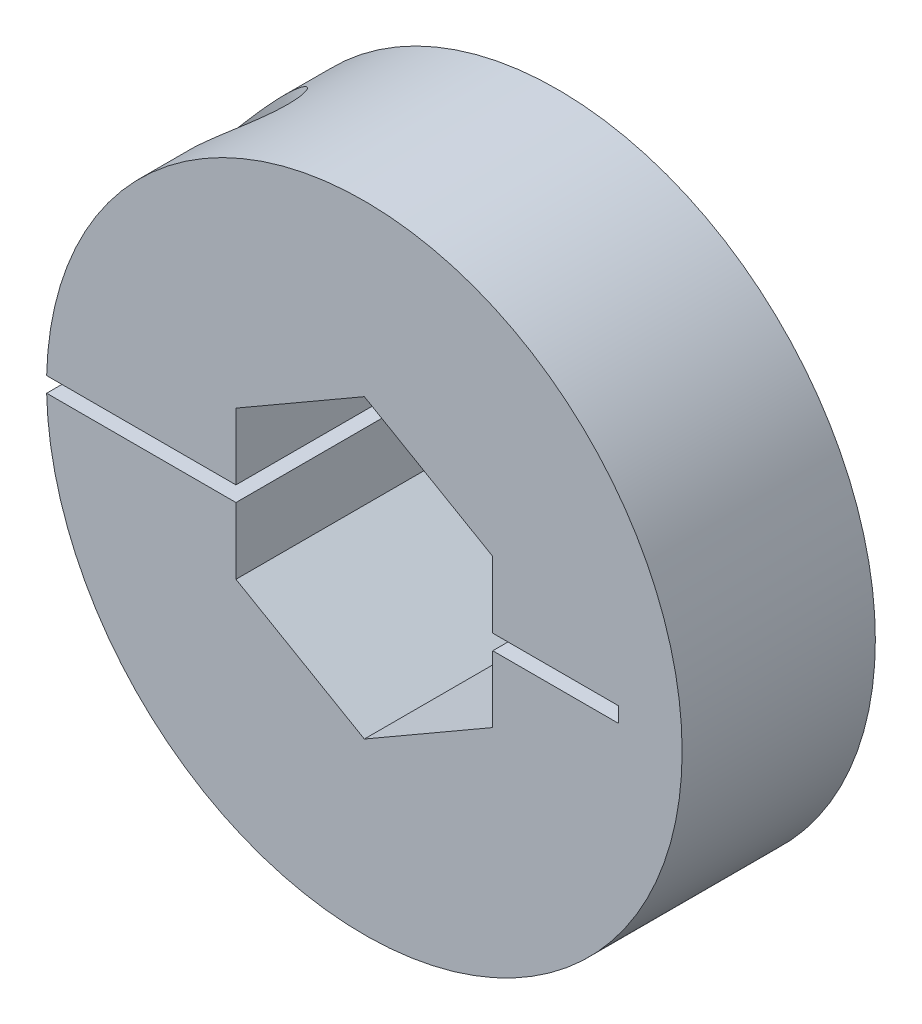
SolidWorks part; units mm, degrees
material "6061 Alloy"
ref_plane "Front Plane" through (0, 0, 0) normal (0, 0, 1) x (1, 0, 0)
ref_plane "Top Plane" through (0, 0, 0) normal (0, 1, 0) x (1, 0, 0)
ref_plane "Right Plane" through (0, 0, 0) normal (1, 0, 0) x (0, 0, -1)
sketch "Sketch1" plane through (0, 0, 0) normal (0, 0, 1) x (1, 0, 0)
  circle A0 centre (0, 0) radius 15.875
  dimension "D1" = 31.75
extrude "Boss-Extrude1" add sketch "Sketch1" along normal mid plane 9.652
sketch "Sketch2" plane through (0, 0, 4.826) normal (0, 0, 1) x (1, 0, 0)
  line L0 (-6.4135, 3.7028) -> (-6.4135, -3.7028)
  line L1 (6.4135, 3.7028) -> (6.4135, -3.7028)
  line L2 (-6.4135, -3.7028) -> (0, -7.4057)
  line L3 (0, -7.4057) -> (6.4135, -3.7028)
  line L4 (-6.4135, 3.7028) -> (0, 7.4057)
  line L5 (0, 7.4057) -> (6.4135, 3.7028)
  point P4 (0, 0)
  point P7 (0, 0)
  point P9 (6.4135, 0)
  point P10 (-6.4135, 0)
  dimension "D1" = 12.827
  dimension "D2" = 12.827
extrude "Cut-Extrude1" cut sketch "Sketch2" against normal through all
sketch "Sketch3" plane through (0, 0, 4.826) normal (0, 0, 1) x (1, 0, 0)
  line L1 (-15.8704, 0.381) -> (12.7, 0.381)
  line L3 (-15.8704, -0.381) -> (12.7, -0.381)
  line L4 (12.7, 0.381) -> (12.7, -0.381)
  circle A0 centre (0, 0) radius 15.875 construction
  arc A1 (-15.8704, 0.381) -> (-15.8704, -0.381) centre (0, 0) ccw
  dimension "D1" = 0.762
  dimension "D2" = 0.381
  dimension "D3" = 12.7
extrude "Cut-Extrude2" cut sketch "Sketch3" against normal through all
sketch "Sketch4" plane through (0, 0, 0) normal (0, 1, 0) x (1, 0, 0)
  line L0 (-15.8704, 4.826) -> (-15.8704, -4.826) construction
  circle A0 centre (-11.0444, 0) radius 2.3876
  dimension "D2" = 4.7752
  dimension "D1" = 4.826
extrude "Cut-Extrude3" cut sketch "Sketch4" against normal through all and the other way through all
